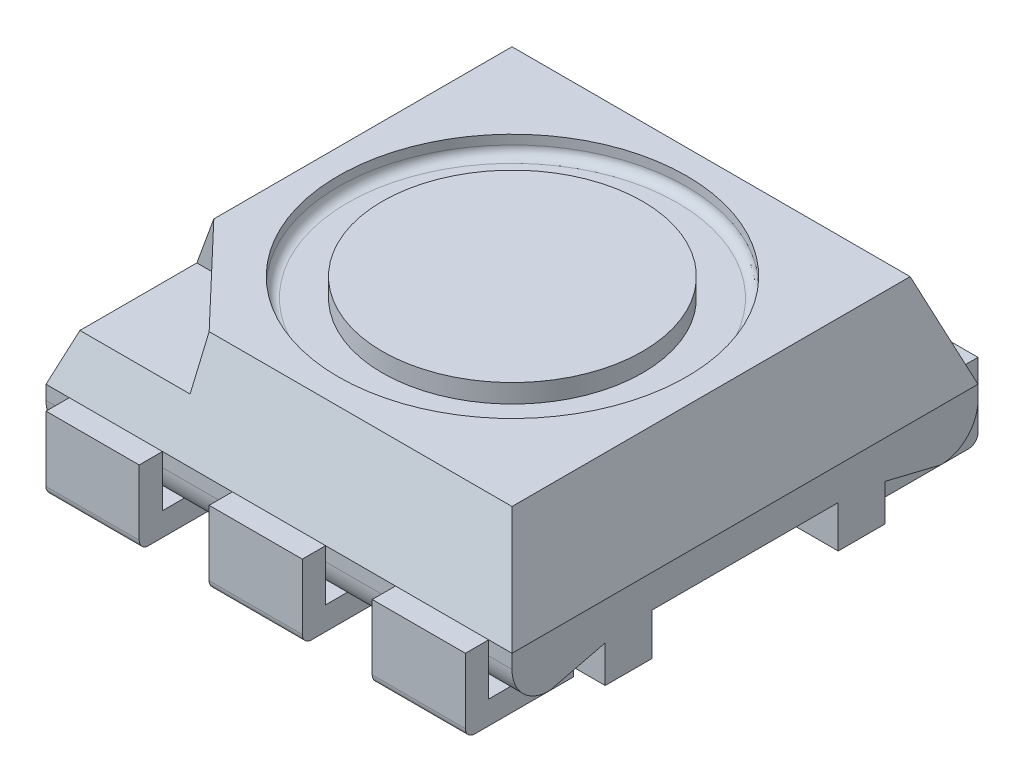
SolidWorks part; units mm, degrees
ref_plane "Front Plane" through (0, 0, 0) normal (0, 0, 1) x (1, 0, 0)
ref_plane "Top Plane" through (0, 0, 0) normal (0, 1, 0) x (1, 0, 0)
ref_plane "Right Plane" through (0, 0, 0) normal (1, 0, 0) x (0, 0, -1)
sketch "Sketch2" plane through (0, 0, 0) normal (0, 1, 0) x (1, 0, 0)
  line L0 (-1.5515, -0.3128) -> (3.4485, -0.3128) construction
  line L1 (-1.5515, 2.1872) -> (3.4485, 2.1872)
  line L2 (-1.5515, 2.1872) -> (-1.5515, -2.8128)
  line L3 (-1.5515, -2.8128) -> (3.4485, -2.8128)
  line L4 (3.4485, 2.1872) -> (3.4485, -2.8128)
  line L5 (0.9485, 2.1872) -> (0.9485, -2.8128) construction
  dimension "D1" = 5
  dimension "D2" = 5
extrude "Boss-Extrude1" add sketch "Sketch2" along normal blind 1
draft "Draft7" type of draft neutral plane draft angle 20 faces to draft 4 face at (0.9485, 0.5, 2.8128) face at (-1.5515, 0.5, 0.3128) face at (3.4485, 0.5, 0.3128) face at (0.9485, 0.5, -2.1872) neutral plane through (0, 0, 0) neutral plane normal (0, -1, 0) reverse direction yes parameters "D1"=20
sketch "Sketch11" plane through (0, 0, 0) normal (0, -1, 0) x (1, 0, 0)
  line L1 (3.4485, 2.8128) -> (-1.5515, 2.8128)
  line L2 (3.4485, 2.8128) -> (3.4485, -2.1872)
  line L3 (3.4485, -2.1872) -> (-1.5515, -2.1872)
  line L4 (-1.5515, 2.8128) -> (-1.5515, -2.1872)
extrude "Boss-Extrude2" add sketch "Sketch11" along normal blind 0.8
sketch "Sketch12"
other "AlignGroup1"
sketch "Sketch13" plane through (0, -0.8, 0) normal (0, -1, 0) x (1, 0, 0)
  line L0 (3.4485, 0.3128) -> (-1.5515, 0.3128) construction
  line L2 (-1.5515, 1.3128) -> (3.4485, 1.3128)
  line L7 (-1.5515, 1.3128) -> (-1.5515, -0.6872)
  line L8 (-1.5515, -0.6872) -> (3.4485, -0.6872)
  line L9 (3.4485, -2.1872) -> (3.4485, 2.8128) construction
  line L10 (-1.5515, 1.7128) -> (3.4485, 1.7128)
  line L11 (-1.5515, 1.7128) -> (-1.5515, -1.0872)
  line L12 (-1.5515, -1.0872) -> (3.4485, -1.0872)
  line L13 (3.4485, 1.7128) -> (3.4485, -1.0872)
  line L14 (-1.5515, 2.8128) -> (-1.5515, -2.1872) construction
  line L15 (3.4485, 1.3128) -> (3.4485, -0.6872)
  point P10 (3.4485, 0.3128)
  point P11 (3.4485, 0.3128)
  dimension "D1" = 2.8
  dimension "D2" = 2
extrude "Cut-Extrude2" cut sketch "Sketch13" against normal blind 0.45 contours L2 L15 L8 L7
sketch "Sketch16" plane through (0, -0.8, 0) normal (0, -1, 0) x (1, 0, 0)
  line L0 (3.4485, 1.3128) -> (3.4485, -0.6872) construction
  line L5 (-2.4225, 1.8128) -> (4.5777, 1.8128)
  line L6 (-2.4225, 1.8128) -> (-2.4225, -1.1872)
  line L7 (-2.4225, -1.1872) -> (4.5777, -1.1872)
  line L8 (4.5777, 1.8128) -> (4.5777, -1.1872)
  line L9 (-1.5515, 0.3128) -> (3.4485, 0.3128) construction
  line L10 (-1.5515, 1.3128) -> (-1.5515, -0.6872) construction
  line L12 (-2.4225, 1.8128) -> (3.9284, 1.8128)
  line L13 (-2.4225, 1.8128) -> (-2.4225, 2.9643)
  line L14 (-2.4225, 2.9643) -> (3.9284, 2.9643)
  line L15 (3.9284, 1.8128) -> (3.9284, 2.9643)
  line L16 (-2.4225, -1.1872) -> (4.339, -1.1872)
  line L17 (-2.4225, -1.1872) -> (-2.4225, -2.4303)
  line L18 (-2.4225, -2.4303) -> (4.339, -2.4303)
  line L19 (4.339, -1.1872) -> (4.339, -2.4303)
  point P6 (4.5777, 0.3128)
  dimension "D1" = 3
extrude "Cut-Extrude3" cut sketch "Sketch16" against normal blind 0.25 contours L12 L15 L14 L13 | L16 L19 L18 L17
sketch "Sketch17" plane through (0, -0.55, 0) normal (0, -1, 0) x (1, 0, 0)
  line L0 (-1.5515, 1.8128) -> (-1.5515, 2.8128) construction
  line L1 (-1.5515, 2.5312) -> (4.0008, 2.5312)
  line L2 (-1.5515, 2.5312) -> (-1.5515, -1.9688)
  line L3 (-1.5515, -1.9688) -> (4.0008, -1.9688)
  line L4 (4.0008, 2.5312) -> (4.0008, -1.9688)
  line L5 (-1.5515, 0.2812) -> (3.4343, 0.2812) construction
  point P8 (4.0008, 0.2812)
  dimension "D1" = 4.5
fillet "Fillet11" radius 0.4 1 edges at (0.9485, -0.55, 2.8128)
fillet "Fillet12" radius 0.4 1 edges at (0.9485, -0.55, -2.1872)
sketch "Sketch22" plane through (0, -0.55, 0) normal (0, -1, 0) x (1, 0, 0)
  line L1 (3.4485, -1.1872) -> (-1.5515, -1.1872)
  line L2 (3.4485, -1.1872) -> (3.4485, -1.7872)
  line L3 (3.4485, -1.7872) -> (-1.5515, -1.7872)
  line L4 (-1.5515, -1.1872) -> (-1.5515, -1.7872)
sketch "Sketch24" plane through (3.4485, 0, 0) normal (1, 0, 0) x (0, 0, -1)
  line L0 (1.1872, -0.55) -> (1.1872, -0.8) construction
  line L1 (-1.8128, -0.55) -> (1.1872, -0.55)
  line L2 (-1.8128, -0.55) -> (-1.8128, -0.4031)
  line L3 (-1.8128, -0.4031) -> (1.1872, -0.4031)
  line L4 (1.1872, -0.55) -> (1.1872, -0.4031)
  line L5 (-2.4128, -0.55) -> (-1.8128, -0.4031)
  line L6 (1.7872, -0.55) -> (1.1872, -0.4031)
  line L7 (-2.4128, -0.55) -> (-1.8128, -0.55)
  line L8 (1.1872, -0.4031) -> (1.1872, -0.55)
  line M3 (1.1872, -0.55) -> (1.7872, -0.55)
  line M9 (-2.4128, -0.55) -> (-1.8128, -0.55)
extrude "Cut-Extrude4" cut sketch "Sketch24" against normal blind 5 contours L5 L2 M9 | L6 L4 M3
sketch "Sketch25" plane through (-1.5515, 0, 0) normal (-1, 0, 0) x (0, 0, 1)
  line L0 (2.8128, 0) -> (3.0628, 0)
  line L1 (3.0628, 0) -> (3.0628, -0.7)
  line L2 (2.9628, -0.8) -> (1.9037, -0.8)
  line L3 (1.9037, -0.8) -> (1.9037, -0.55)
  line L4 (2.5312, -0.55) -> (-1.9688, -0.55) construction
  line L5 (1.9037, -0.55) -> (2.8128, -0.55)
  line L6 (2.8128, -0.55) -> (2.8128, 0)
  arc A0 (2.9628, -0.8) -> (3.0628, -0.7) centre (2.9628, -0.7) ccw
  point P5 (0, 0)
  point P11 (0, 0)
  point P12 (0, 0)
  dimension "D1" = 0.1
extrude "Boss-Extrude9" add sketch "Sketch25" against normal blind 1 from offset 2 separate body contours L2 L3 L5 L6 L0 L1 A0 offset against normal yes
pattern_linear "LPattern2" count 2 spacing 1.75 along (1, 0, 0) count 2 spacing 1.75 along (-1, 0, 0) of "Boss-Extrude9"
pattern_circular "CirPattern6" count 2 over 360 about axis through (0.9485, 0, 0.3128) along (0, 1, 0) of bodies 116 107 117
sketch "Sketch28" plane through (0, 1, 0) normal (0, 1, 0) x (1, 0, 0)
  line L0 (0.9485, 1.8233) -> (0.9485, -2.439) construction
  line L1 (3.0846, 1.8233) -> (-1.1875, 1.8233) construction
  line L2 (-1.1875, -0.3128) -> (3.0846, -0.3128) construction
  line L3 (-1.1875, 1.8233) -> (-1.1875, -2.4488) construction
  line L4 (3.0846, -2.4488) -> (3.0846, 1.8233) construction
  circle A0 centre (0.9485, -0.3078) radius 1.8682
  circle A1 centre (0.9485, -0.3078) radius 1.1921
extrude "Cut-Extrude5" cut sketch "Sketch28" against normal blind 0.2 contours A0
sketch "Sketch30" plane through (0, 0.8, 0) normal (0, 1, 0) x (1, 0, 0)
  circle A0 centre (0.9485, -0.3078) radius 1.8682 construction
  circle A1 centre (0.9485, -0.3078) radius 1.3958
  point P0 (0.9485, -0.3078)
extrude "Boss-Extrude10" add sketch "Sketch30" along normal blind 0.2
fillet "Fillet14" radius 0.1 1 edges at (0.9485, 0.8, 2.1761)
sketch "Sketch31" plane through (0, 1, 0) normal (0, 1, 0) x (1, 0, 0)
  line L0 (-1.1875, -1.3761) -> (-0.1649, -2.4488)
  line L1 (-1.1875, 1.8233) -> (-1.1875, -2.4488) construction
  line L2 (-1.1875, -2.4488) -> (3.0846, -2.4488) construction
  line L3 (-1.1875, -1.3761) -> (-2.3945, -1.3761)
  line L4 (-2.3945, -1.3761) -> (-2.6008, -3.636)
  line L5 (-2.6008, -3.636) -> (-0.3272, -3.7589)
  line L6 (-0.3272, -3.7589) -> (-0.1649, -2.4488)
extrude "Cut-Extrude6" cut sketch "Sketch31" against normal blind 0.5
move or copy body "Body-Move/Copy2"
sketch "Sketch32" plane through (0, 1.8, 0) normal (0, 1, 0) x (1, 0, 0)
  circle A0 centre (0.9485, -0.3078) radius 1.3958 construction
  point P0 (0.9485, -0.3078)
  point P1 (0, 0)
  point P4 (0, 0)
move or copy body "Body-Move/Copy3"
move or copy body "Body-Move/Copy4"
move or copy body "Body-Move/Copy5"
